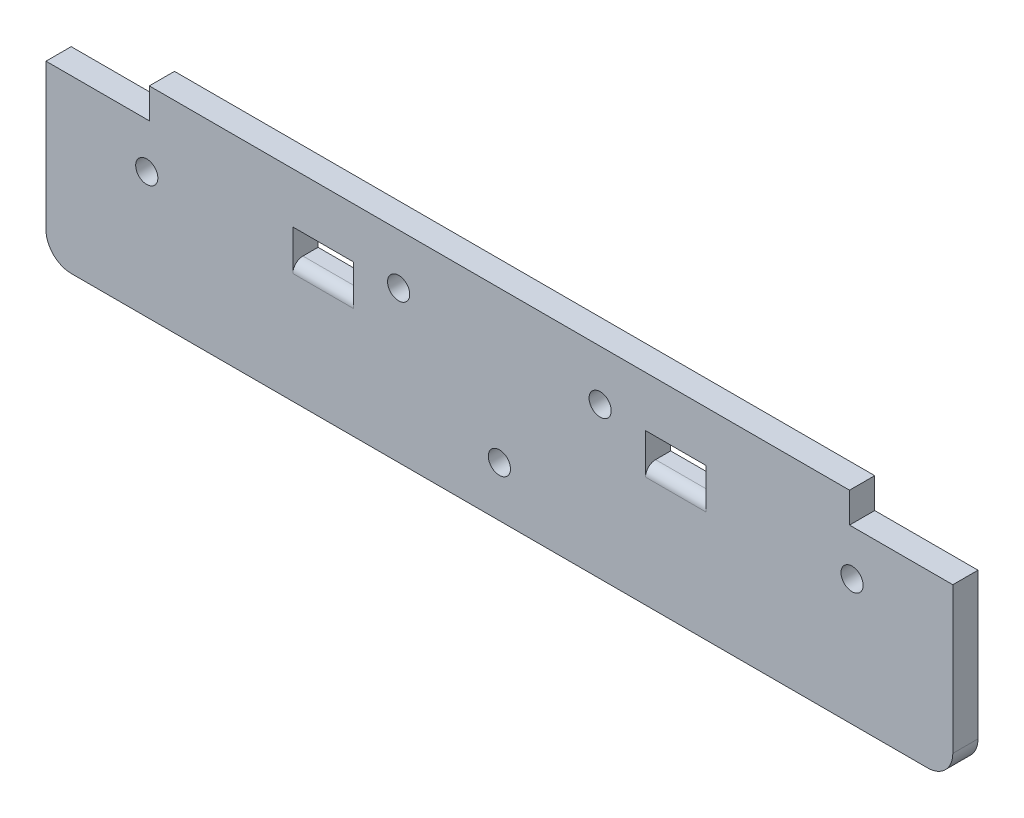
SolidWorks part; units mm, degrees
ref_plane "Płaszczyzna przednia" through (0, 0, 0) normal (0, 0, 1) x (1, 0, 0)
ref_plane "Płaszczyzna górna" through (0, 0, 0) normal (0, 1, 0) x (1, 0, 0)
ref_plane "Płaszczyzna prawa" through (0, 0, 0) normal (1, 0, 0) x (0, 0, -1)
sketch "Szkic1" plane through (0, 0, 0) normal (0, 0, 1) x (1, 0, 0)
  line L1 (-90, -20) -> (90, -20)
  line L2 (-90, -20) -> (-90, 20)
  line L3 (-90, 20) -> (90, 20)
  line L4 (90, -20) -> (90, 20)
  line L5 (-90, -20) -> (90, 20) construction
  line L6 (-90, 20) -> (90, -20) construction
  point P0 (0, 0)
  dimension "D1" = 40
  dimension "D2" = 180
extrude "Dodanie-wyciągnięcie1" add sketch "Szkic1" along normal blind 5
fillet "Zaokrąglenie1" radius 5 4 edges at (-90, 20, 2.5) (-90, -20, 2.5) (90, -20, 2.5) (90, 20, 2.5)
sketch "Szkic2" plane through (0, 0, 5) normal (0, 0, 1) x (1, 0, 0)
  line L0 (-90, 15) -> (-90, -15) construction
  line L1 (90, -15) -> (90, 15) construction
  line L2 (85, 20) -> (-85, 20) construction
  circle A0 centre (-70, 5) radius 2.2
  circle A1 centre (-20, 10) radius 2.2
  circle A2 centre (20, 10) radius 2.2
  circle A3 centre (70, 5) radius 2.2
  dimension "D1" = 40
  dimension "D4" = 20
  dimension "D6" = 4.4
  dimension "D7" = 10
  dimension "D2" = 20
  dimension "D3" = 20
  dimension "D5" = 15
extrude "Wytnij-wyciągnięcie1" cut sketch "Szkic2" against normal blind 5
sketch "Szkic3" plane through (0, 0, 5) normal (0, 0, 1) x (1, 0, 0)
  line L0 (-90, 15) -> (-90, -15) construction
  line L1 (-90, 20) -> (-69.5, 20)
  line L2 (-90, 20) -> (-90, 14)
  line L3 (-90, 14) -> (-69.5, 14)
  line L4 (-69.5, 20) -> (-69.5, 14)
  line L5 (85, 20) -> (-85, 20) construction
  line L6 (90, -15) -> (90, 15) construction
  line L7 (90, 20) -> (69.5, 20)
  line L8 (90, 20) -> (90, 14)
  line L9 (90, 14) -> (69.5, 14)
  line L10 (69.5, 20) -> (69.5, 14)
  dimension "D1" = 6
  dimension "D2" = 20.5
  dimension "D3" = 6
extrude "Wytnij-wyciągnięcie2" cut sketch "Szkic3" against normal blind 10
sketch "Szkic4" plane through (0, 0, 5) normal (0, 0, 1) x (1, 0, 0)
  line L0 (-85, -20) -> (85, -20) construction
  circle A0 centre (0, -10) radius 2.2
  point P5 (0, -20)
  dimension "D1" = 10
  dimension "D2" = 4.4
extrude "Wytnij-wyciągnięcie3" cut sketch "Szkic4" against normal blind 10
sketch "Szkic5" plane through (0, 0, 5) normal (0, 0, 1) x (1, 0, 0)
  line L1 (-41, 10) -> (-29, 10)
  line L2 (-41, 10) -> (-41, 4)
  line L3 (-41, 4) -> (-29, 4)
  line L4 (-29, 10) -> (-29, 4)
  line L5 (29, 10) -> (41, 10)
  line L6 (29, 10) -> (29, 4)
  line L7 (29, 4) -> (41, 4)
  line L8 (41, 10) -> (41, 4)
  circle A0 centre (0, -10) radius 2.2 construction
  dimension "D7" = 14
  dimension "D1" = 6
  dimension "D2" = 12
  dimension "D3" = 6
  dimension "D4" = 12
  dimension "D5" = 29
  dimension "D6" = 14
  dimension "D8" = 29
extrude "Wytnij-wyciągnięcie4" cut sketch "Szkic5" against normal through all
fillet "Zaokrąglenie2" radius 2 2 edges at (-35, 4, 5) (35, 4, 5)
